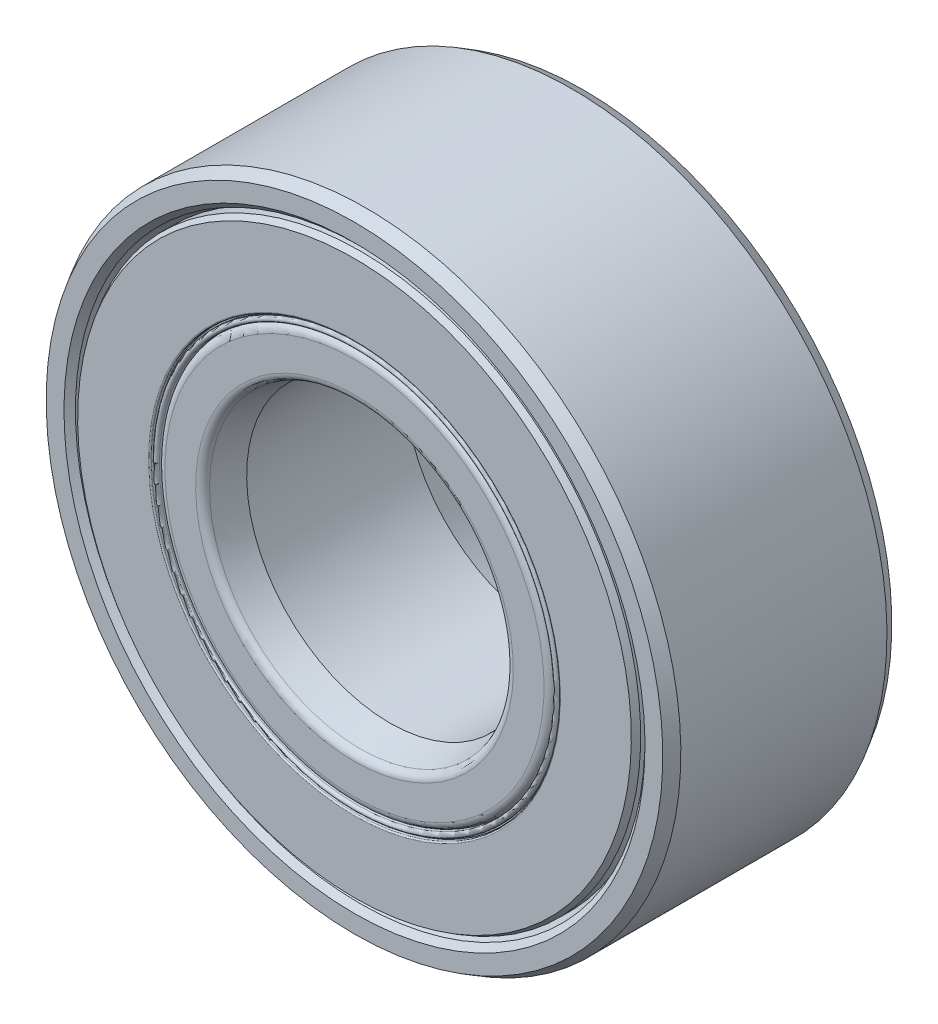
SolidWorks part; units mm, degrees
ref_plane "Front Plane" through (0, 0, 0) normal (0, 0, 1) x (1, 0, 0)
ref_plane "Top Plane" through (0, 0, 0) normal (0, 1, 0) x (1, 0, 0)
ref_plane "Right Plane" through (0, 0, 0) normal (1, 0, 0) x (0, 0, -1)
sketch "Sketch1" plane through (0, 0, 0) normal (0, 0, 1) x (1, 0, 0)
  line L0 (-5.5, 0) -> (5.5, 0) construction
  line L1 (-2.5, 0) -> (2.5, 0) construction
  circle A0 centre (0, 0) radius 2.5 construction
  circle A1 centre (0, 0) radius 5.5 construction
  point P3 (0, 0)
  point P6 (0, 0)
  point P7 (0, -2.5)
  point P11 (0, -5.5)
  point P12 (0, 2.5)
  point P13 (0, 5.5)
  dimension "OD" = 11
  dimension "ID" = 5
sketch "Sketch2" plane through (0, 0, 0) normal (1, 0, 0) x (0, 0, -1)
  line L0 (-2, 5.5) -> (2, 5.5) construction
  line L1 (0, 5.5) -> (0, -5.5) construction
  line L2 (1.8, 5.5) -> (-1.8, 5.5)
  line L3 (-1.8, 5.5) -> (-2, 5.3845)
  line L4 (-2, 5.3845) -> (-2, 5.074)
  line L5 (-1.683, 4.895) -> (-0.863, 4.895)
  line L6 (1.683, 4.895) -> (0.863, 4.895)
  line L7 (2, 5.3845) -> (2, 5.074)
  line L8 (1.8, 5.5) -> (2, 5.3845)
  line L9 (-0.863, 4.895) -> (-0.863, 5.0967) construction
  line L10 (-0.863, 5.0967) -> (-0.863, 5.2983) construction
  line L11 (0, 5.5) -> (0, -5.5) construction
  line L12 (-2, 0) -> (2, 0) construction
  line L13 (2, 2.5) -> (-2, 2.5) construction
  line L14 (-2, 2.5) -> (-2, -2.5) construction
  line L15 (-2, -2.5) -> (2, -2.5) construction
  line L16 (2, 5.5) -> (2, -5.5) construction
  line L17 (-0.863, 5.2983) -> (-0.863, 5.5) construction
  line L18 (-0.863, 5.2983) -> (0, 5.2983) construction
  line L20 (-1.683, 4.895) -> (-1.9, 4.974)
  line L21 (-1.9, 4.974) -> (-2, 5.074)
  line L26 (1.9, 4.974) -> (2, 5.074)
  line L27 (1.683, 4.895) -> (1.9, 4.974)
  arc A0 (-0.863, 4.895) -> (0.863, 4.895) centre (0, 4.1733) cw
  circle A1 centre (0, 4.1733) radius 1.125 construction
  point P17 (0, 0)
  point P21 (0, 5.5)
  point P30 (0, -2.5)
  dimension "Approx. Ball Dia." = 2.25
  dimension "Width" = 4
  dimension "For Shaft Diameter" = 5
  dimension "For Housing ID" = 11
  dimension "D4" = 9.79
  dimension "D2" = 20
  dimension "D5" = 45
  dimension "D1" = 30
  dimension "D6" = 0.2
  dimension "D7" = 0.1
sketch "Sketch3" plane through (0, 0, 0) normal (1, 0, 0) x (0, 0, -1)
  line L14 (-1.683, 4.895) -> (-1.9, 4.974) construction
  line L15 (-1.9, 4.974) -> (-2, 5.074) construction
  line L16 (-2, 5.3845) -> (-2, 5.074) construction
  line L17 (-1.8, 5.5) -> (-2, 5.3845) construction
  line L18 (1.8, 5.5) -> (-1.8, 5.5) construction
  line L19 (1.8, 5.5) -> (2, 5.3845) construction
  line L20 (2, 5.3845) -> (2, 5.074) construction
  line L21 (1.9, 4.974) -> (2, 5.074) construction
  line L22 (1.683, 4.895) -> (1.9, 4.974) construction
  line L23 (1.683, 4.895) -> (0.863, 4.895) construction
  line L24 (-1.683, 4.895) -> (-0.863, 4.895) construction
  line L25 (-1.683, 4.895) -> (-1.9, 4.974)
  line L26 (-1.9, 4.974) -> (-2, 5.074)
  line L27 (-2, 5.3845) -> (-2, 5.074)
  line L28 (-1.8, 5.5) -> (-2, 5.3845)
  line L29 (1.8, 5.5) -> (-1.8, 5.5)
  line L30 (1.8, 5.5) -> (2, 5.3845)
  line L31 (2, 5.3845) -> (2, 5.074)
  line L32 (1.9, 4.974) -> (2, 5.074)
  line L33 (1.683, 4.895) -> (1.9, 4.974)
  line L34 (1.683, 4.895) -> (0.863, 4.895)
  line L35 (-1.683, 4.895) -> (-0.863, 4.895)
  arc A2 (0.863, 4.895) -> (-0.863, 4.895) centre (0, 4.1733) ccw construction
  arc A3 (0.863, 4.895) -> (-0.863, 4.895) centre (0, 4.1733) ccw
revolve "Revolve1" add sketch "Sketch3" angle 360 about L12
sketch "Sketch4" plane through (0, 0, 0) normal (1, 0, 0) x (0, 0, -1)
  line L0 (0, 5.5) -> (0, -5.5) construction
  line L1 (0, 5.5) -> (0, -5.5) construction
  line L2 (-1.3832, 2.5) -> (-1.8948, 2.6371)
  line L3 (-2, 2.7742) -> (-2, 3.3097)
  line L4 (2, -5.3845) -> (2, 5.3845) construction
  line L5 (-1.8581, 3.4517) -> (-0.863, 3.4517)
  line L6 (-1.3832, 2.5) -> (1.3832, 2.5)
  line L7 (2, 5.3845) -> (2, 5.074) construction
  line L8 (1.3832, 2.5) -> (1.8948, 2.6371)
  line L9 (0, 5.2983) -> (0, 2.5) construction
  line L10 (2, 2.7742) -> (2, 3.3097)
  line L11 (1.8581, 3.4517) -> (0.863, 3.4517)
  line L12 (1.3832, 2.5) -> (1.3832, 2.6371) construction
  line L13 (1.3832, 2.6371) -> (1.3832, 2.7742) construction
  line L14 (1.3832, 2.7742) -> (1.3832, 2.9112) construction
  line L15 (1.3832, 2.9112) -> (1.3832, 3.0483) construction
  circle A0 centre (0, 4.1733) radius 1.125 construction
  arc A1 (0.863, 3.4517) -> (-0.863, 3.4517) centre (0, 4.1733) cw
  arc A2 (2, 3.3097) -> (1.8581, 3.4517) centre (1.8581, 3.3097) ccw
  arc A3 (-2, 3.3097) -> (-1.8581, 3.4517) centre (-1.8581, 3.3097) cw
  arc A4 (1.8948, 2.6371) -> (2, 2.7742) centre (1.8581, 2.7742) ccw
  arc A5 (-1.8948, 2.6371) -> (-2, 2.7742) centre (-1.8581, 2.7742) cw
  point P14 (2, 2.6653)
  point P36 (0, 3.0483)
  dimension "D1" = 15
revolve "Revolve2" add sketch "Sketch4" angle 360 about L12
sketch "Sketch5" plane through (0, 0, 0) normal (1, 0, 0) x (0, 0, -1)
  line L0 (-1.125, 4.1733) -> (1.125, 4.1733)
  arc A2 (-1.125, 4.1733) -> (1.125, 4.1733) centre (0, 4.1733) cw
  arc A3 (0.863, 4.895) -> (-0.863, 4.895) centre (0, 4.1733) ccw construction
revolve "Revolve3" add sketch "Sketch5" angle 360 about L0
pattern_circular "CirPattern1" count 9 over 360 about axis through (0, 0, 0) along (0, 0, 1) of bodies 104
sketch "Sketch6" plane through (0, 0, 0) normal (1, 0, 0) x (0, 0, -1)
  line L1 (-1.8961, 4.895) -> (-1.125, 4.895)
  line L2 (-2, 4.835) -> (-2, 3.5957)
  line L3 (-1.976, 3.5717) -> (-1.125, 3.5717)
  line L4 (-1.125, 4.895) -> (-1.125, 3.5717)
  line L5 (-2, 2.7742) -> (-2, 3.3097) construction
  line L6 (-1.8, 5.5) -> (-2, 5.3845) construction
  line L7 (0, 5.5) -> (0, 2.5) construction
  line L8 (1.976, 3.5717) -> (1.125, 3.5717)
  line L9 (1.125, 4.895) -> (1.125, 3.5717)
  line L10 (1.8961, 4.895) -> (1.125, 4.895)
  line L11 (2, 4.835) -> (2, 3.5957)
  line L13 (-1.8581, 3.4517) -> (-0.863, 3.4517) construction
  line L14 (-2, 4.835) -> (-1.8961, 4.895)
  line L15 (-1.683, 4.895) -> (-0.863, 4.895) construction
  line L16 (2, 4.835) -> (1.8961, 4.895)
  arc A0 (-2, 3.5957) -> (-1.976, 3.5717) centre (-1.976, 3.5957) ccw
  circle A1 centre (0, 4.1733) radius 1.125 construction
  arc A2 (2, 3.5957) -> (1.976, 3.5717) centre (1.976, 3.5957) cw
  point P26 (-2, 3.5717)
  dimension "D3" = 0.024
  dimension "D1" = 0.12
  dimension "D2" = 0.06
revolve "Revolve4" add sketch "Sketch6" angle 360 about L12
sketch "Sketch7" plane through (0, 0, 0) normal (1, 0, 0) x (0, 0, -1)
  line L3 (-1.125, 3.5717) -> (-1.9026, 3.5717)
  line L4 (-1.976, 3.5717) -> (-1.125, 3.5717) construction
  line L7 (0, 3.0483) -> (0, 2.5) construction
  line L8 (0, 5.5) -> (0, -5.5) construction
  line L21 (-1.9026, 3.5717) -> (-1.9322, 3.5665)
  line L22 (-1.93, 3.5417) -> (-1.955, 3.5417)
  line L23 (-1.955, 3.4517) -> (-1.125, 3.4517)
  line L24 (-1.125, 3.4517) -> (-1.125, 3.5717)
  line L25 (-1.8581, 3.4517) -> (-0.863, 3.4517) construction
  line L26 (-2, 3.5957) -> (-2, 3.4517) construction
  line L27 (-2, 3.4517) -> (-1.955, 3.4517) construction
  line L28 (-1.9026, 3.5717) -> (-1.9026, 3.5417) construction
  line L29 (-1.9026, 3.5417) -> (-1.9026, 3.5117) construction
  line L30 (-1.9026, 3.5117) -> (-1.9026, 3.4817) construction
  line L31 (-1.9026, 3.4817) -> (-1.9026, 3.4517) construction
  circle A2 centre (0, 4.1733) radius 1.125 construction
  arc A9 (-1.9322, 3.5665) -> (-1.93, 3.5417) centre (-1.93, 3.5542) ccw
  arc A10 (-1.955, 3.5417) -> (-1.955, 3.4517) centre (-1.955, 3.4967) ccw
  dimension "D1" = 0.025
  dimension "D2" = 10
revolve "Revolve5" add sketch "Sketch7" angle 360 about L12
equation "\"D4@Sketch2\"=\"OD@Sketch1\"*.89"
equation "\"D1@Sketch6\"=(\"OD@Sketch1\"-\"ID@Sketch1\")*.02"
equation "\"D2@Sketch6\"=\"D1@Sketch6\"*.5"
equation "\"D3@Sketch6\"=\"D1@Sketch6\"*.2"
equation "\"D6@Sketch2\"=\"Width@Sketch2\"*.05"
equation "\"D7@Sketch2\"=\"D6@Sketch2\"*.5"
equation "\"D1@CirPattern1\" =  ( pi * \"OD@Sketch1\" )  * .5625 / \"Approx. Ball Dia.@Sketch2\""
equation "\"Approx. Ball Dia.@Sketch2\"=(\"OD@Sketch1\"-\"ID@Sketch1\")*.5*.75"
